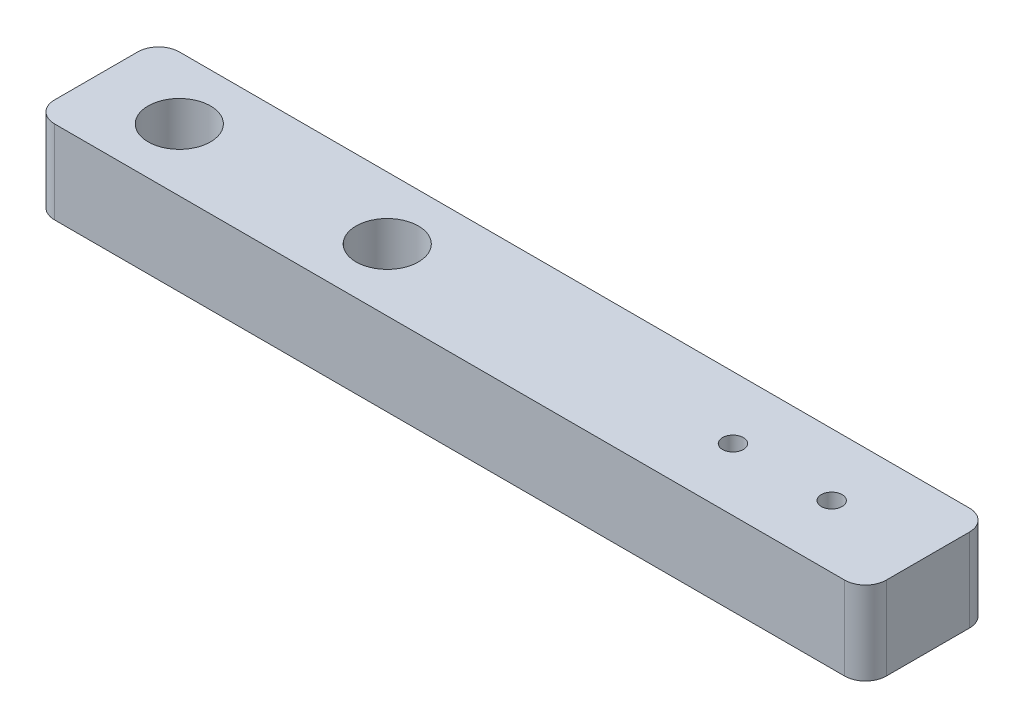
SolidWorks part; units mm, degrees
ref_plane "Front Plane" through (0, 0, 0) normal (0, 0, 1) x (1, 0, 0)
ref_plane "Top Plane" through (0, 0, 0) normal (0, 1, 0) x (1, 0, 0)
ref_plane "Right Plane" through (0, 0, 0) normal (1, 0, 0) x (0, 0, -1)
sketch "Sketch1" plane through (0, 0, 0) normal (0, 1, 0) x (1, 0, 0)
  line L1 (-40, -6) -> (40, -6)
  line L2 (-40, -6) -> (-40, 6)
  line L3 (-40, 6) -> (40, 6)
  line L4 (40, -6) -> (40, 6)
  line L5 (-40, -6) -> (40, 6) construction
  line L6 (-40, 6) -> (40, -6) construction
  point P0 (0, 0)
  dimension "D1" = 80
  dimension "D2" = 12
extrude "Boss-Extrude1" add sketch "Sketch1" along normal blind 8
sketch "Sketch2" plane through (0, 8, 0) normal (0, 1, 0) x (1, 0, 0)
  line L0 (-40, 6) -> (-40, -6) construction
  line L1 (21.25, 0) -> (30.75, 0) construction
  circle A0 centre (-32, 0) radius 3
  circle A1 centre (-12, 0) radius 3
  circle A2 centre (21.25, 0) radius 1
  circle A3 centre (30.75, 0) radius 1
  point P11 (26, 0)
  dimension "D2" = 6
  dimension "D4" = 2
  dimension "D1" = 20
  dimension "D3" = 8
  dimension "D5" = 9.5
  dimension "D6" = 38
extrude "Cut-Extrude1" cut sketch "Sketch2" against normal through all
fillet "Fillet1" radius 2 4 edges at (-40, 4, -6) (40, 4, -6) (40, 4, 6) (-40, 4, 6)
